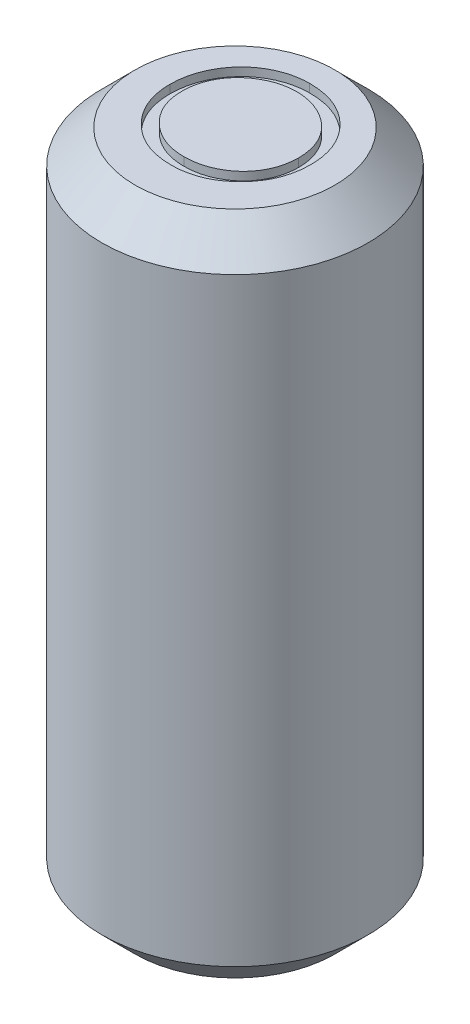
SolidWorks part; units mm, degrees
ref_plane "Front Plane" through (0, 0, 0) normal (0, 0, 1) x (1, 0, 0)
ref_plane "Top Plane" through (0, 0, 0) normal (0, 1, 0) x (1, 0, 0)
ref_plane "Right Plane" through (0, 0, 0) normal (1, 0, 0) x (0, 0, -1)
sketch "Sketch1" plane through (0, 0, 0) normal (0, 1, 0) x (1, 0, 0)
  circle A0 centre (0, 0) radius 4
  dimension "D1" = 8
extrude "Boss-Extrude1" add sketch "Sketch1" along normal blind 20
chamfer "Chamfer1" distance 1 angle 45 2 edges at (0, 0, 4) (0, 20, 4)
sketch "Sketch2" plane through (0, 20, 0) normal (0, 1, 0) x (1, 0, 0)
  text T0 "X" font "Century Gothic" height 4
extrude "Cut-Extrude1" [suppressed] cut sketch "Sketch2" against normal blind 0.25
sketch "Sketch3" plane through (0, 20, 0) normal (0, 1, 0) x (1, 0, 0)
  text T0 "O" font "Century Gothic" height 4
extrude "Cut-Extrude2" cut sketch "Sketch3" against normal blind 0.25
